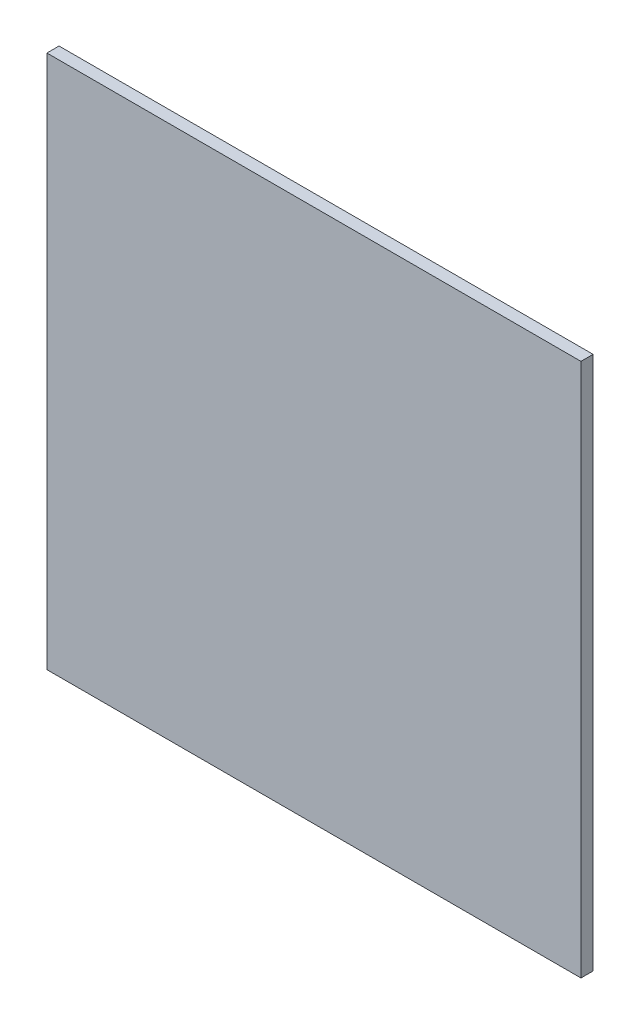
SolidWorks part; units mm, degrees
ref_plane "Plan de face" through (0, 0, 0) normal (0, 0, 1) x (1, 0, 0)
ref_plane "Plan de dessus" through (0, 0, 0) normal (0, 1, 0) x (1, 0, 0)
ref_plane "Plan de droite" through (0, 0, 0) normal (1, 0, 0) x (0, 0, -1)
sketch "Esquisse1" plane through (0, 0, 0) normal (0, 0, 1) x (1, 0, 0)
  line L1 (22, -22) -> (-22, -22)
  line L2 (22, -22) -> (22, 22)
  line L3 (22, 22) -> (-22, 22)
  line L4 (-22, -22) -> (-22, 22)
  line L5 (22, -22) -> (-22, 22) construction
  line L6 (22, 22) -> (-22, -22) construction
  point P0 (0, 0)
  dimension "D1" = 44
  dimension "D2" = 44
extrude "Boss.-Extru.1" add sketch "Esquisse1" along normal blind 1
